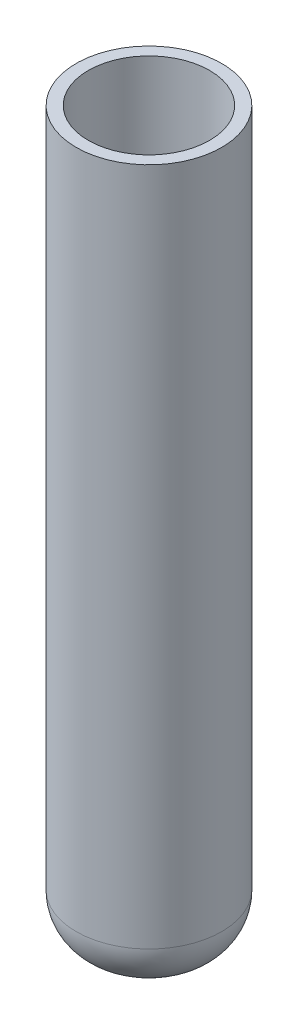
SolidWorks part; units mm, degrees
ref_plane "前视基准面" through (0, 0, 0) normal (0, 0, 1) x (1, 0, 0)
ref_plane "上视基准面" through (0, 0, 0) normal (0, 1, 0) x (1, 0, 0)
ref_plane "右视基准面" through (0, 0, 0) normal (1, 0, 0) x (0, 0, -1)
sketch "草图1" plane through (0, 0, 0) normal (0, 1, 0) x (1, 0, 0)
  circle A0 centre (0, 0) radius 3
  dimension "D1" = 6
extrude "凸台-拉伸1" add sketch "草图1" along normal blind 30
fillet "圆角1" radius 2 1 edges at (0, 0, 3)
shell "抽壳1" thickness 0.5
